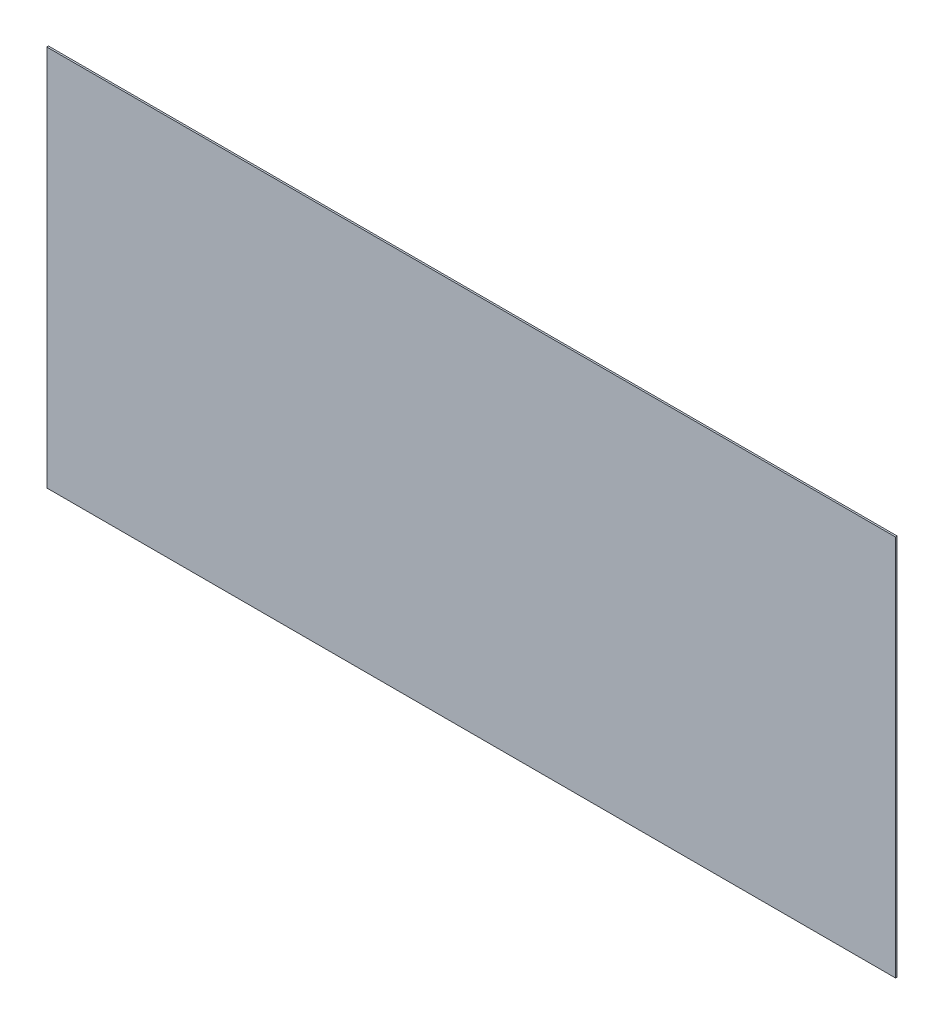
SolidWorks part; units mm, degrees
ref_plane "前视基准面" through (0, 0, 0) normal (0, 0, 1) x (1, 0, 0)
ref_plane "上视基准面" through (0, 0, 0) normal (0, 1, 0) x (1, 0, 0)
ref_plane "右视基准面" through (0, 0, 0) normal (1, 0, 0) x (0, 0, -1)
sketch "草图1" plane through (0, 0, 0) normal (0, 0, 1) x (1, 0, 0)
  line L1 (-500, 225) -> (500, 225)
  line L2 (-500, 225) -> (-500, -225)
  line L3 (-500, -225) -> (500, -225)
  line L4 (500, 225) -> (500, -225)
  line L5 (-500, 225) -> (500, -225) construction
  line L6 (-500, -225) -> (500, 225) construction
  point P0 (0, 0)
  dimension "D1" = 450
  dimension "D2" = 1000
extrude "凸台-拉伸1" add sketch "草图1" along normal blind 2
